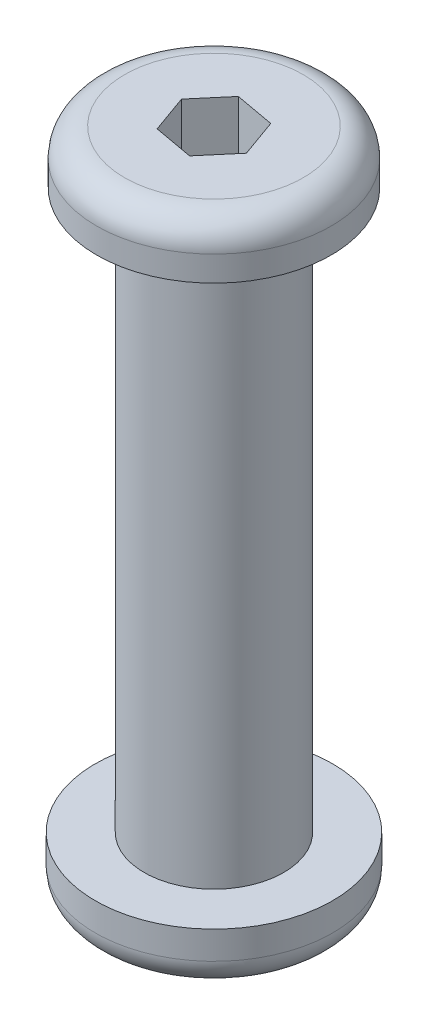
SolidWorks part; units mm, degrees
material "AISI 304"
ref_plane "前视基准面" through (0, 0, 0) normal (0, 0, 1) x (1, 0, 0)
ref_plane "上视基准面" through (0, 0, 0) normal (0, 1, 0) x (1, 0, 0)
ref_plane "右视基准面" through (0, 0, 0) normal (1, 0, 0) x (0, 0, -1)
other "Configuration Table"
sketch "草图1" plane through (0, 0, 0) normal (0, 1, 0) x (1, 0, 0)
  circle A0 centre (0, 0) radius 2.5
  dimension "D1" = 5
extrude "凸台-拉伸1" add sketch "草图1" along normal blind 20
sketch "草图2" plane through (0, 20, 0) normal (0, 1, 0) x (1, 0, 0)
  line L1 (0.9335, 1.1008) -> (-0.4866, 1.3589)
  line L2 (-0.4866, 1.3589) -> (-1.4201, 0.258)
  line L3 (-1.4201, 0.258) -> (-0.9335, -1.1008)
  line L4 (-0.9335, -1.1008) -> (0.4866, -1.3589)
  line L5 (0.4866, -1.3589) -> (1.4201, -0.258)
  line L6 (1.4201, -0.258) -> (0.9335, 1.1008)
  circle A0 centre (0, 0) radius 4.2
  circle A1 centre (0, 0) radius 1.25 construction
  dimension "D1" = 8.4
  dimension "D2" = 2.5
extrude "凸台-拉伸2" add sketch "草图2" along normal blind 1.9
sketch "草图3" plane through (0, 0, 0) normal (0, -1, 0) x (1, 0, 0)
  line L1 (0.8318, 1.1796) -> (-0.6057, 1.3102)
  line L2 (-0.6057, 1.3102) -> (-1.4375, 0.1305)
  line L3 (-1.4375, 0.1305) -> (-0.8318, -1.1796)
  line L4 (-0.8318, -1.1796) -> (0.6057, -1.3102)
  line L5 (0.6057, -1.3102) -> (1.4375, -0.1305)
  line L6 (1.4375, -0.1305) -> (0.8318, 1.1796)
  circle A0 centre (0, 0) radius 4.25
  circle A1 centre (0, 0) radius 1.25 construction
  dimension "D1" = 8.5
  dimension "D2" = 2.5
extrude "凸台-拉伸3" add sketch "草图3" along normal blind 2
fillet "圆角1" radius 1 2 edges at (0, 21.9, 4.2) (0, -2, -4.25)
